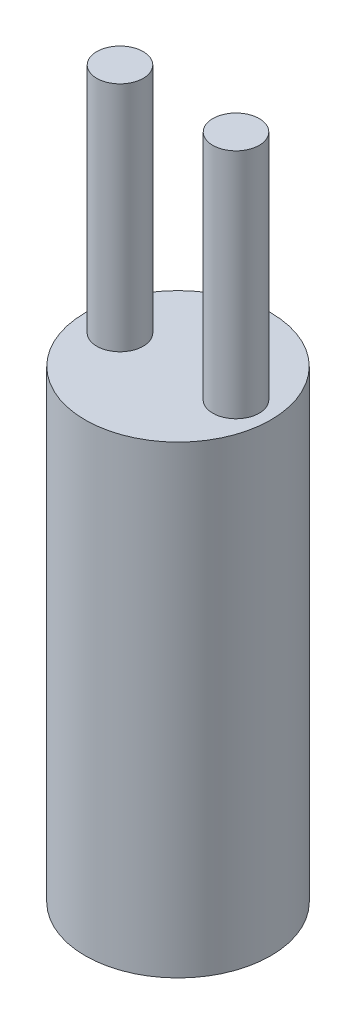
SolidWorks part; units mm, degrees
ref_plane "前视基准面" through (0, 0, 0) normal (0, 0, 1) x (1, 0, 0)
ref_plane "上视基准面" through (0, 0, 0) normal (0, 1, 0) x (1, 0, 0)
ref_plane "右视基准面" through (0, 0, 0) normal (1, 0, 0) x (0, 0, -1)
other "Configuration Table"
sketch "草图1" plane through (0, 0, 0) normal (0, 1, 0) x (1, 0, 0)
  circle A0 centre (0, 0) radius 4
  dimension "D1" = 8
extrude "凸台-拉伸1" add sketch "草图1" along normal blind 20
sketch "草图2" plane through (0, 20, 0) normal (0, 1, 0) x (1, 0, 0)
  circle A0 centre (-2.5, 0) radius 1
  point P2 (0, 0)
  dimension "D1" = 2
  dimension "D2" = 2.5
extrude "凸台-拉伸2" add sketch "草图2" along normal blind 10
mirror "镜向1" about plane through (0, 0, 0) normal (1, 0, 0) of "凸台-拉伸2"
